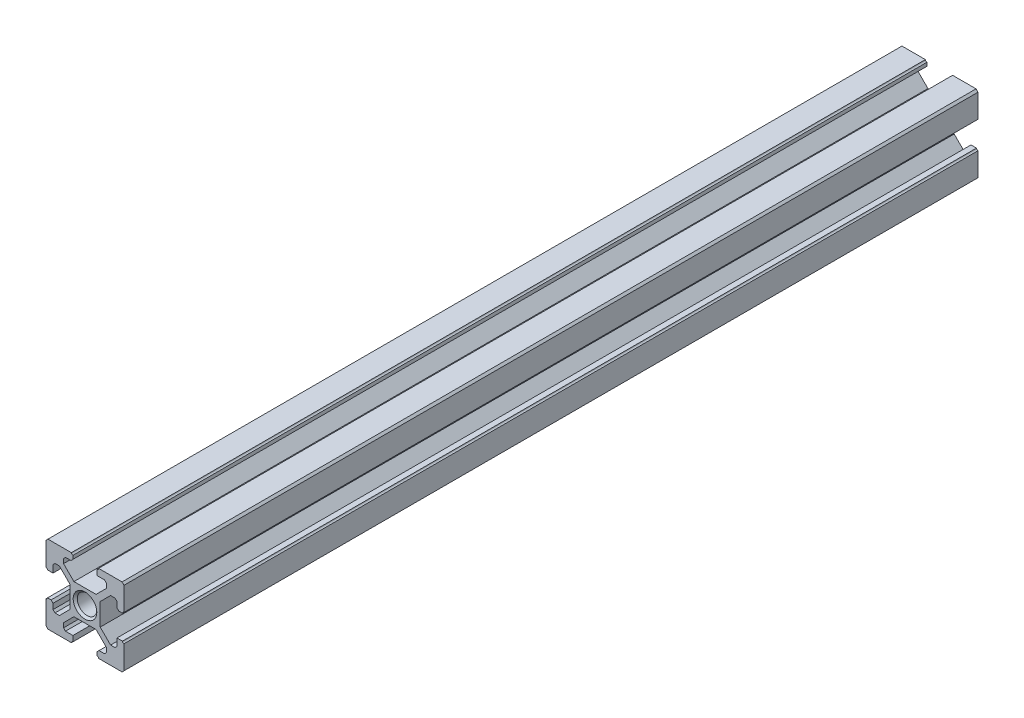
SolidWorks part; units mm, degrees
ref_plane "Front Plane" through (0, 0, 0) normal (0, 0, 1) x (1, 0, 0)
ref_plane "Top Plane" through (0, 0, 0) normal (0, 1, 0) x (1, 0, 0)
ref_plane "Right Plane" through (0, 0, 0) normal (1, 0, 0) x (0, 0, -1)
sketch "Sketch1" plane through (0, 0, 0) normal (0, 0, 1) x (1, 0, 0)
  line L0 (0, 10.7337) -> (0, 0.7337) construction
  line L1 (-9.5, 10) -> (-3.4865, 10)
  line L2 (-10, 9.5) -> (-10, 3.4865)
  line L3 (-9.5, -10) -> (-3.4865, -10)
  line L4 (10, 9.5) -> (10, 3.4865)
  line L5 (-9.75, 9.75) -> (9.75, -9.75) construction
  line L6 (-9.75, -9.75) -> (10, 10) construction
  line L7 (0, 0) -> (-10, 0) construction
  line L8 (3.1, 9.6135) -> (3.1, 8.2)
  line L9 (3.1, 8.2) -> (5, 8.2)
  line L10 (5.5, 7.7) -> (5.5, 6.5607)
  line L11 (5.5, 6.5607) -> (2.8393, 3.9)
  line L12 (2.8393, 3.9) -> (0, 3.9)
  line L13 (3.9, 2.8393) -> (3.9, 0)
  line L14 (6.5607, 5.5) -> (3.9, 2.8393)
  line L15 (9.6135, 3.1) -> (8.7, 3.1)
  line L16 (8.2, 3.6) -> (8.2, 5)
  line L17 (7.7, 5.5) -> (6.5607, 5.5)
  line L18 (3.4865, 10) -> (9.5, 10)
  line L19 (10, -3.4865) -> (10, -9.5)
  line L20 (5, 8.2) -> (5.5, 7.7)
  line L21 (8.2, 5) -> (7.7, 5.5)
  line L22 (9.5, 10) -> (10, 9.5)
  line L23 (8.7, 3.1) -> (8.2, 3.6)
  line L24 (3.9, -2.8393) -> (3.9, 0)
  line L25 (6.5607, -5.5) -> (3.9, -2.8393)
  line L26 (7.7, -5.5) -> (6.5607, -5.5)
  line L27 (8.2, -5) -> (7.7, -5.5)
  line L28 (8.2, -3.1) -> (8.2, -5)
  line L29 (9.6135, -3.1) -> (8.2, -3.1)
  line L30 (10, -3.4865) -> (10, -9.5)
  line L31 (10, -9.5) -> (9.5, -10)
  line L32 (9.5, -10) -> (3.4865, -10)
  line L33 (3.1, -9.6135) -> (3.1, -8.7)
  line L34 (3.1, -8.7) -> (3.6, -8.2)
  line L35 (3.6, -8.2) -> (5, -8.2)
  line L36 (5, -8.2) -> (5.5, -7.7)
  line L37 (5.5, -7.7) -> (5.5, -6.5607)
  line L38 (5.5, -6.5607) -> (2.8393, -3.9)
  line L39 (2.8393, -3.9) -> (0, -3.9)
  line L40 (-2.8393, -3.9) -> (0, -3.9)
  line L41 (-5.5, -6.5607) -> (-2.8393, -3.9)
  line L42 (-5.5, -7.7) -> (-5.5, -6.5607)
  line L43 (-5, -8.2) -> (-5.5, -7.7)
  line L44 (-3.1, -8.2) -> (-5, -8.2)
  line L45 (-3.1, -9.6135) -> (-3.1, -8.2)
  line L46 (-3.4865, -10) -> (-9.5, -10)
  line L47 (-9.5, -10) -> (-10, -9.5)
  line L48 (-10, -9.5) -> (-10, -3.4865)
  line L49 (-9.6135, -3.1) -> (-8.7, -3.1)
  line L50 (-8.7, -3.1) -> (-8.2, -3.6)
  line L51 (-8.2, -3.6) -> (-8.2, -5)
  line L52 (-8.2, -5) -> (-7.7, -5.5)
  line L53 (-7.7, -5.5) -> (-6.5607, -5.5)
  line L54 (-6.5607, -5.5) -> (-3.9, -2.8393)
  line L55 (-3.9, -2.8393) -> (-3.9, 0)
  line L56 (-3.9, 2.8393) -> (-3.9, 0)
  line L57 (-6.5607, 5.5) -> (-3.9, 2.8393)
  line L58 (-7.7, 5.5) -> (-6.5607, 5.5)
  line L59 (-8.2, 5) -> (-7.7, 5.5)
  line L60 (-8.2, 3.1) -> (-8.2, 5)
  line L61 (-9.6135, 3.1) -> (-8.2, 3.1)
  line L62 (-10, 3.4865) -> (-10, 9.5)
  line L63 (-10, 9.5) -> (-9.5, 10)
  line L64 (-9.5, 10) -> (-3.4865, 10)
  line L65 (-3.1, 9.6135) -> (-3.1, 8.7)
  line L66 (-3.1, 8.7) -> (-3.6, 8.2)
  line L67 (-3.6, 8.2) -> (-5, 8.2)
  line L68 (-5, 8.2) -> (-5.5, 7.7)
  line L69 (-5.5, 7.7) -> (-5.5, 6.5607)
  line L70 (-5.5, 6.5607) -> (-2.8393, 3.9)
  line L71 (-2.8393, 3.9) -> (0, 3.9)
  line L72 (3.4865, -10) -> (9.5, -10)
  line L73 (-10, -3.4865) -> (-10, -9.5)
  arc A0 (3.1, 9.6135) -> (3.4865, 10) centre (3.1, 10) ccw
  arc A1 (9.6135, 3.1) -> (10, 3.4865) centre (10, 3.1) cw
  arc A2 (9.6135, -3.1) -> (10, -3.4865) centre (10, -3.1) ccw
  arc A3 (3.1, -9.6135) -> (3.4865, -10) centre (3.1, -10) cw
  arc A4 (-3.1, -9.6135) -> (-3.4865, -10) centre (-3.1, -10) ccw
  arc A5 (-9.6135, -3.1) -> (-10, -3.4865) centre (-10, -3.1) cw
  arc A6 (-9.6135, 3.1) -> (-10, 3.4865) centre (-10, 3.1) ccw
  arc A7 (-3.1, 9.6135) -> (-3.4865, 10) centre (-3.1, 10) cw
  point P0 (0, 0)
  point P13 (5.5, 8.2)
  point P17 (3.1, 8.9068)
  point P22 (8.2, 3.1)
  point P23 (8.2, 5.5)
  point P103 (0, 0)
  dimension "D3" = 1.8
  dimension "D4" = 6.1
  dimension "D5" = 11
  dimension "D6" = 6.2
  dimension "D7" = 1.5
extrude "Boss-Extrude1" add sketch "Sketch1" along normal blind 219 contours L65 A7 L1 L63 L2 A6 L61 L60 L59 L58 L57 L56 L55 L54 L53 L52 L51 L50 L49 A5 L48 L47 L3 A4 L45 L44 L43 L42 L41 L40 L39 L38 L37 L36 L35 L34 L33 A3 L32 L31 L19 A2 L29 L28 L27 L26 L25 L24 L13 L14 L17
hole_wizard "M6x1.0 Tapped Hole1" positions "3DSketch1" profile "Sketch2" tap size "M6x1.0" standard "ANSI Metric"
sketch3d "3DSketch1"
  line L0 (3.9, -2.8393, 219) -> (3.9, 2.8393, 219) construction
  line L1 (2.8393, 3.9, 219) -> (-2.8393, 3.9, 219) construction
  point P0 (0, 0, 0)
  point P3 (0, 0, 0)
  point P5 (0, 0, 0)
  point P7 (0.9996, -8.1302, 0)
  point P9 (0, 0, 0)
  point P11 (0, 0, 219)
  dimension "D1" = 3.9
  dimension "D2" = 3.9
sketch "Sketch2" plane through (0, 0, 219) normal (1, 0, 0) x (0, -1, 0)
  line L0 (0, 0) -> (0, 30)
  line L1 (0, 30) -> (2.5, 28.4978)
  line L2 (2.5, 28.4978) -> (2.5, 0.525)
  line L3 (2.5, 0.525) -> (3.025, 0)
  line L5 (3.025, 0) -> (0, 0)
  line L6 (-2.5, 0.525) -> (-3.025, 0) construction
  line L10 (0, 30) -> (-2.5, 28.4978) construction
  line L11 (0, -6.35) -> (0, 107.95) construction
  dimension "Tap Drill Dia." = 5
  dimension "Tap Drill Depth" = 30
  dimension "Near C'Sink Dia." = 6.05
  dimension "Near C'Sink Angle" = 90
  dimension "Drill Angle" = 118
cosmetic thread "Hole Thread6" parameters "D1"=12, "D2"=6
hole_wizard "M6x1.0 Tapped Hole2" positions "3DSketch2" profile "Sketch3" tap size "M6x1.0" standard "ANSI Metric"
sketch3d "3DSketch2"
  line L0 (2.8393, 3.9, 0) -> (-2.8393, 3.9, 0) construction
  line L1 (3.9, -2.8393, 0) -> (3.9, 2.8393, 0) construction
  point P3 (0, 0, 0)
  dimension "D1" = 3.9
  dimension "D2" = 3.9
sketch "Sketch3" plane through (0, 0, 0) normal (1, 0, 0) x (0, 1, 0)
  line L0 (0, 0) -> (0, 30)
  line L1 (0, 30) -> (2.5, 28.4978)
  line L2 (2.5, 28.4978) -> (2.5, 0.525)
  line L3 (2.5, 0.525) -> (3.025, 0)
  line L5 (3.025, 0) -> (0, 0)
  line L6 (-2.5, 0.525) -> (-3.025, 0) construction
  line L10 (0, 30) -> (-2.5, 28.4978) construction
  line L11 (0, -6.35) -> (0, 107.95) construction
  dimension "Tap Drill Dia." = 5
  dimension "Tap Drill Depth" = 30
  dimension "Near C'Sink Dia." = 6.05
  dimension "Near C'Sink Angle" = 90
  dimension "Drill Angle" = 118
cosmetic thread "Hole Thread7" parameters "D1"=12, "D2"=6
